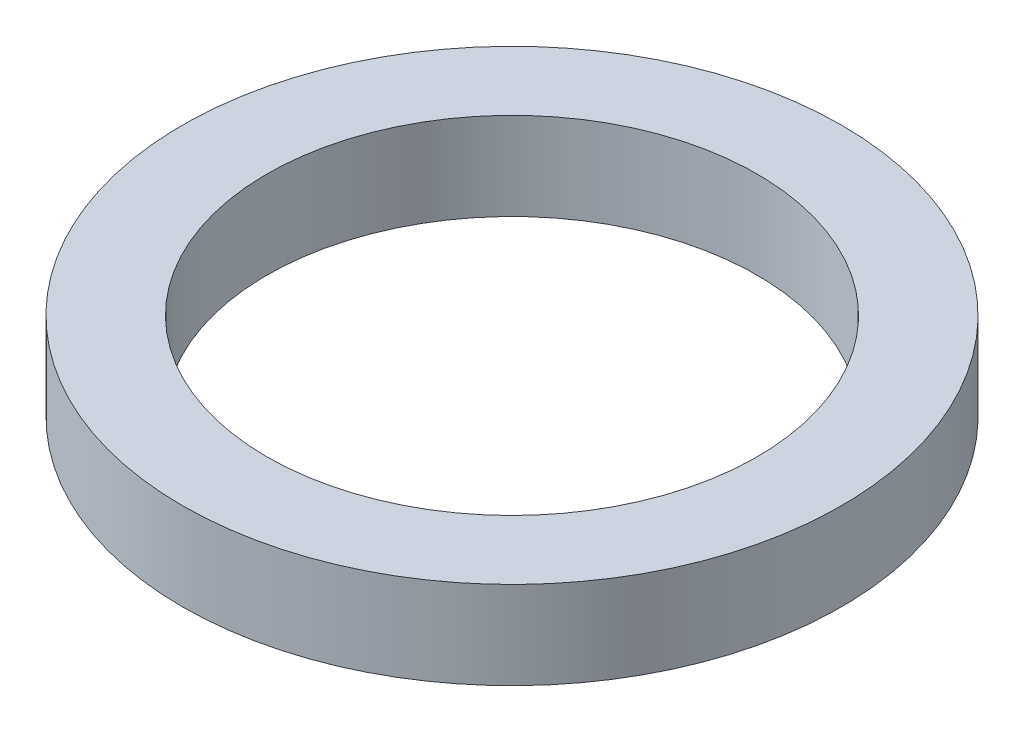
SolidWorks part; units mm, degrees
ref_plane "Front Plane" through (0, 0, 0) normal (0, 0, 1) x (1, 0, 0)
ref_plane "Top Plane" through (0, 0, 0) normal (0, 1, 0) x (1, 0, 0)
ref_plane "Right Plane" through (0, 0, 0) normal (1, 0, 0) x (0, 0, -1)
sketch "Sketch1" plane through (0, 0, 0) normal (0, 1, 0) x (1, 0, 0)
  circle A0 centre (0, 0) radius 26
  circle A1 centre (0, 0) radius 34.965
  dimension "D1" = 52
  dimension "D2" = 69.93
extrude "Boss-Extrude1" add sketch "Sketch1" along normal mid plane 9.3
equation "\"module\"= 1"
equation "\"pressure_angle\"= 20deg"
equation "\"h_a\"= 1 * \"module\"'addendum"
equation "\"h_f\"= 1.25 * \"module\"'dedendum"
equation "\"clr_tip_root\"= \"h_f\" - \"h_a\"'clearance of gear tooth tip and root"
equation "\"bearing_ID\"= \"module\" * ( \"Ns\" + \"Np_b\") + 6"
equation "\"bearing_OD\"= 1.18 * \"bearing_ID\" + 8.57"
equation "\"bearing_height\"= 0.09 * \"bearing_ID\" + 4.62"
equation "\"clearance_planet\"=1.5"
equation "\"case_dist\"= \"sec_carrier_thickness\" + \"clearance_planet\" + \"sun_coupler_hub_thickness\" - \"case_mounting_surface_height\""
equation "\"Motor_case_OD_max\"= \"case_mounting_PCD\" + \"case_mounting_hole_allen_socket_dia\" + \"clearance_case_mount_holes_shell_thickness\" * 2"
equation "\"case_mounting_PCD\"= \"motor_case_OD_base\" + \"case_mounting_hole_shift\" * 2"
equation "\"bearing mount thickness\"= IIF((\"bearing_OD\" + \"output_mounting_hole_dia\" * 4) > (\"Nr_s\" * \"module\" + 2 * \"h_b\"), \"output_mounting_hole_dia\" * 2, ((\"Nr_s\" * \"module\" + 2 * \"h_b\" - (\"bearing_OD\" + \"output_mounting_hole_dia\" * 4)) / 2) + \"output_mounting_hole_dia\" * 2 + \"standard_clearance_1_5mm\")"
equation "\"case_mounting_hole_dia\"=3"
equation "\"output_mounting_PCD\"= \"bearing_OD\" + \"bearing mount thickness\""
equation "\"output_mounting_hole_dia\"= 4"
equation "\"clearance_case_mount_holes_shell_thickness\"= 1"
equation "\"motor_case_OD_base\"= \"motor_OD\" + \"clearance_motor_and_case\" * 2 + \"Motor_case_thickness\" * 2"
equation "\"sec_carrier_thickness\"= 5"
equation "\"sun_coupler_hub_thickness\"= 4"
equation "\"clearance_sun_coupler_sec_carrier\"= 1.5"
equation "\"clearance_motor_and_case\"= IIF( ((\"Ns\" + \"Np_b\" * 2) * \"module\") < \"motor_OD\", 5, (((\"Ns\" + \"Np_b\" * 2) * \"module\" - \"motor_OD\") * 0.5 + 5) )"
equation "\"motor_OD\"= 72"
equation "\"Motor_case_thickness\"= 2.5"
equation "\"Motor_case_ID\"= \"motor_OD\" + \"clearance_motor_and_case\" * 2"
equation "\"case_mounting_hole_shift\"= \"case_mounting_hole_dia\" / 2 - 0.5"
equation "\"output_mounting_nut_wrench_size\"= 7"
equation "\"output_mounting_nut_thickness\"= 3.2"
equation "\"case_mounting_hole_allen_socket_dia\"= 5.5"
equation "\"output_mounting_nut_depth\"= 3"
equation "\"case_mounting_bolt_depth\"= 4.5"
equation "\"Ns\"= 20"
equation "\"ring_radial_thickness\"= 5"
equation "\"ring_to_chamfer_clearance\"= \"clearance_planet\""
equation "\"Motor_case_OD_base_to_chamfer\"=5"
equation "\"pattern_offset_from_motor_case_OD_base\"= 3"
equation "\"pattern_bulge_dia\"= 3"
equation "\"pattern_num_bulge\"= 18"
equation "\"pattern_depth\"= 2"
equation "\"motor_height\"= 27"
equation "\"case_mounting_wrench_size\"= 5.5"
equation "\"case_mounting_nut_clearance\"= 2"
equation "\"base_plate_thickness\"= 4"
equation "\"case_mounting_nut_thickness\"= 2.4"
equation "\"case_mounting_surface_height\"= 4"
equation "\"motor_mount_hole_PCD\"= 32"
equation "\"motor_mount_hole_dia\"= 4"
equation "\"motor_mount_hole_num\"= 4"
equation "\"central_hole_offset_from_motor_mount_PCD\"= 5"
equation "\"wire_slot_dist_from_center\"= 33"
equation "\"wire_slot_length\"= 10"
equation "\"wire_slot_radius\"= 4"
equation "\"driver_upper_holes_dist_from_center\"= 23"
equation "\"driver_lower_holes_dist_from_center\"= 15"
equation "\"driver_side_holes_dist_from_center\"= 20"
equation "\"driver_mount_holes_dia\"= 2.5"
equation "\"driver_mount_inserts_OD\"= 3.5"
equation "\"driver_mount_thickness\"= 1.5"
equation "\"driver_mount_height\"= 4"
equation "\"air_flow_hole_offset\"= 3"
equation "\"num_planet\"= 4"
equation "\"planet_pin_bolt_dia\"= 5"
equation "\"planet_pin_socket_head_dia\"= 8.5"
equation "\"carrier_PCD\"= ( \"Np_b\" + \"Ns\" ) * \"module\""
equation "\"planet_shaft_dia\"= 8"
equation "\"planet_shaft_step_offset\"= 1"
equation "\"carrier_trapezoidal_support_sun_offset\"= 5"
equation "\"carrier_trapezoidal_support_hole_PCD_offset_bearing_ID\"= 4"
equation "\"carrier_trapezoidal_support_hole_dia\"= 3"
equation "\"carrier_trapezoidal_support_hole_socket_head_dia\"= 5.5"
equation "\"carrier_bearing_step_width\"= 1.5"
equation "\"standard_clearance_1_5mm\"=1.5"
equation "\"standard_fillet_1_5mm\"= 1.5"
equation "\"sun_shaft_bearing_OD\"= 12"
equation "\"sun_shaft_bearing_width\"= 3.5"
equation "\"standard_bearing_insertion_chamfer\"= 0.5"
equation "\"D1@Sketch1\"=\"bearing_ID\""
equation "\"D2@Sketch1\"=\"bearing_OD\""
equation "\"D1@Boss-Extrude1\"=\"bearing_height\""
equation "\"carrier_trapezoidal_support_hole_wrench_size\"= 5.5"
equation "\"planet_pin_bolt_wrench_size\"= 8"
equation "\"Np_b\"= 26"
equation "\"pressure angle\"= 20deg"
equation "\"h_b\"= 1.25 * \"module\"'dedendum"
equation "\"dp_s\"= \"module\" * \"Ns\"'PCD"
equation "\"db_s\"= \"dp_s\" * cos ( \"pressure angle\" )'base CD"
equation "\"fw_s_calc\"= 10mm'face width"
equation "\"alpha_s\"= sqr ( \"dp_s\" ^ 2 - \"db_s\" ^ 2 ) / \"db_s\" * 180 / pi - \"pressure angle\""
equation "\"beta_s\"= ( 360 / ( 4 * \"Ns\" ) - \"alpha_s\" ) * 2"
equation "\"dp_p_b\"= \"module\" * \"Np_b\"'PCD"
equation "\"db_p_b\"= \"dp_p_b\" * cos ( \"pressure angle\" )'base CD"
equation "\"fw_p_s\"= \"fw_r_s\" + \"clearance_planet\""
equation "\"alpha_p_b\"= sqr ( \"dp_p_b\" ^ 2 - \"db_p_b\" ^ 2 ) / \"db_p_b\" * 180 / pi - \"pressure angle\""
equation "\"beta_p_b\"= ( 360 / ( 4 * \"Np_b\" ) - \"alpha_p_b\" ) * 2"
equation "\"planet_bearing_OD\"= 12"
equation "\"planet_bearing_width\"= 3.5"
equation "\"planet_bore\"= 10"
equation "\"motor_output_hole_PCD\"= 22"
equation "\"motor_output_hole_dia\"= 3"
equation "\"motor_output_hole_num\"= 4"
equation "\"sun_shaft_bearing_ID\"= 8"
equation "\"sun_hub_dia\"= \"motor_output_hole_PCD\" + \"motor_output_hole_dia\" + \"standard_clearance_1_5mm\" * 2"
equation "\"sun_central_bolt_dia\"= 5"
equation "\"sun_central_bolt_socket_head_dia\"= 8.5"
equation "\"fw_s_used\"= \"fw_p_s\" + \"fw_p_b\" + \"clearance_planet\" + \"sec_carrier_thickness\" + \"standard_clearance_1_5mm\" - \"carrier_small_ring_inner_bearing_flap\" +  \"standard_clearance_1_5mm\" "
equation "\"motor_output_hole_CSK_OD\"= 9'8.96 is exact value"
equation "\"motor_output_hole_CSK_head_height\"= 2.5"
equation "\"bearing_retainer_thickness\"= 2"
equation "\"Np_s\"= 22"
equation "\"fw_p_b\"= 8"
equation "\"dp_p_s\"= \"module\" * \"Np_s\"'PCD"
equation "\"db_p_s\"= \"dp_p_s\" * cos ( \"pressure angle\" )'base CD"
equation "\"alpha_p_s\"= sqr ( \"dp_p_s\" ^ 2 - \"db_p_s\" ^ 2 ) / \"db_p_s\" * 180 / pi - \"pressure angle\""
equation "\"beta_p_s\"= ( 360 / ( 4 * \"Np_s\" ) - \"alpha_p_s\" ) * 2"
equation "\"Nr_b\"= \"Ns\" + \"Np_b\" * 2"
equation "\"dp_r_b\"= \"module\" * \"Nr_b\"'PCD"
equation "\"db_r_b\"= \"dp_r_b\" * cos ( \"pressure_angle\" )'base CD"
equation "\"fw_r_b\"= \"fw_p_b\"'face width"
equation "\"alpha_r_b\"= sqr ( \"dp_r_b\" ^ 2 - \"db_r_b\" ^ 2 ) / \"db_r_b\" * 180 / pi - \"pressure_angle\""
equation "\"beta_r_b\"= ( 360 / ( 4 * \"Nr_b\" ) + \"alpha_r_b\" ) * 2"
equation "\"ring_OD_b\"= \"Nr_b\" * \"module\" + \"ring_radial_thickness\" * 2"
equation "\"Fillet10\"= IIF ( \"ring_OD_b\" > ( \"bearing_OD\" + 2 * \"bearing mount thickness\" ) , \"suppressed\" , \"unsuppressed\" )"
equation "\"Fillet11\"= IIF ( \"ring_OD_b\" < ( \"bearing_OD\" + 2 * \"bearing mount thickness\" ) , \"suppressed\" , \"unsuppressed\" )"
equation "\"Nr_s\"= \"Ns\" + \"Np_b\" + \"Np_s\"'num teeth"
equation "\"clr_tip_root_s\"= \"h_f\" - \"h_a\"'clearance of gear tooth tip and root"
equation "\"dp_r_s\"= \"module\" * \"Nr_s\"'PCD"
equation "\"db_r_s\"= \"dp_r_s\" * cos ( \"pressure_angle\" )'base CD"
equation "\"fw_r_s\"= 8mm'face width"
equation "\"alpha_r_s\"= sqr ( \"dp_r_s\" ^ 2 - \"db_r_s\" ^ 2 ) / \"db_r_s\" * 180 / pi - \"pressure_angle\""
equation "\"beta_r_s\"= ( 360 / ( 4 * \"Nr_s\" ) + \"alpha_r_s\" ) * 2"
equation "\"small_ring_case_thickness\"= 4mm"
equation "\"carrier_thickness\"= 4mm"
equation "\"small_ring_output_wall_thickness\"= 5mm"
equation "\"small_ring_output_wall_to_bearing_shaft_attachement_hole_dia\"= 4mm"
equation "\"small_ring_output_wall_to_bearing_shaft_attachement_hole_depth\"= 6.5mm"
equation "\"small_ring_output_wall_to_bearing_shaft_attachement_nut_wrench\"= 7mm"
equation "\"small_ring_output_wall_to_bearing_shaft_attachement_nut_thickness\"= 3.2mm"
equation "\"small_ring_output_wall_to_bearing_shaft_attachement_hole_pcd\"= 12mm"
equation "\"small_ring_output_wall_to_bearing_shaft_attachement_hole_num\"= 3"
equation "\"small_ring_output_wall_to_bearing_shaft_attachement_hole_CSK_OD\"= 9mm"
equation "\"small_ring_output_wall_to_bearing_shaft_attachement_hole_CSK_head_height\"= 2.5mm"
equation "\"carrier_small_ring_inner_bearing_ID\"= 20mm"
equation "\"carrier_small_ring_inner_bearing_OD\"= 32mm"
equation "\"carrier_small_ring_inner_bearing_height\"= 7mm"
equation "\"carrier_small_ring_inner_bearing_flap\"= 2mm"
equation "\"gear_casing_big_ring_to_bearing_dist\"=\"fw_p_s\" + \"clearance_planet\" + \"carrier_thickness\" + \"standard_clearance_1_5mm\"*2/3 + \"small_ring_case_thickness\" "
equation "\"gear_casing_thickness\"= 4"
